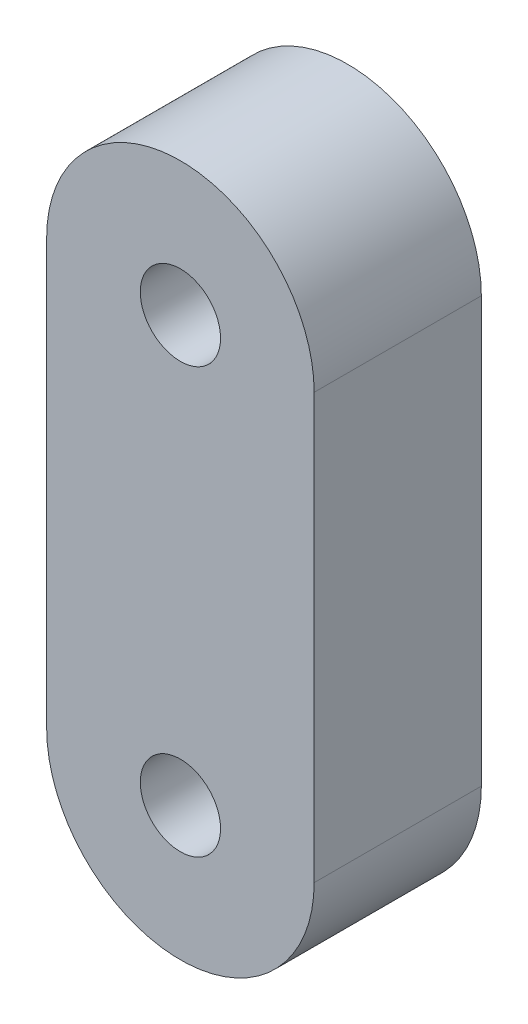
SolidWorks part; units mm, degrees
material "Thornel Mat VMA"
ref_plane "前视基准面" through (0, 0, 0) normal (0, 0, 1) x (1, 0, 0)
ref_plane "上视基准面" through (0, 0, 0) normal (0, 1, 0) x (1, 0, 0)
ref_plane "右视基准面" through (0, 0, 0) normal (1, 0, 0) x (0, 0, -1)
sketch "草图1" plane through (0, 0, 0) normal (0, 0, 1) x (1, 0, 0)
  line L0 (0, -6.35) -> (0, 6.35) construction
  line L5 (-4, -6.35) -> (-4, 6.35)
  line L6 (4, -6.35) -> (4, 6.35)
  arc A0 (-4, -6.35) -> (4, -6.35) centre (0, -6.35) ccw
  arc A1 (4, 6.35) -> (-4, 6.35) centre (0, 6.35) ccw
  circle A2 centre (0, 6.35) radius 1.2
  circle A3 centre (0, -6.35) radius 1.2
  point P2 (0, 0)
  dimension "D2" = 2.4
  dimension "D3" = 4
  dimension "D1" = 12.7
extrude "凸台-拉伸1" add sketch "草图1" along normal blind 5
